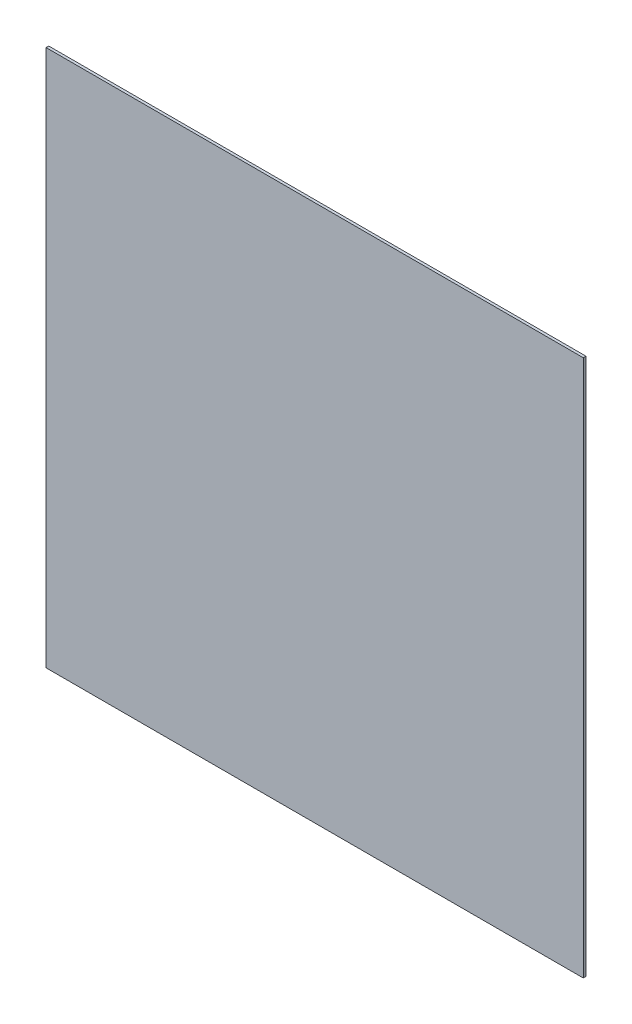
SolidWorks part; units mm, degrees
ref_plane "Front Plane" through (0, 0, 0) normal (0, 0, 1) x (1, 0, 0)
ref_plane "Top Plane" through (0, 0, 0) normal (0, 1, 0) x (1, 0, 0)
ref_plane "Right Plane" through (0, 0, 0) normal (1, 0, 0) x (0, 0, -1)
sketch "Sketch1" plane through (0, 0, 0) normal (0, 0, 1) x (1, 0, 0)
  line L0 (-500, -1008) -> (-500, -8) construction
  line L1 (500, -1008) -> (-500, -1008)
  line L2 (500, -1008) -> (500, -8)
  line L3 (500, -8) -> (-500, -8)
  line L4 (-500, -1008) -> (-500, -8)
  line L5 (500, -1008) -> (-500, -8) construction
  line L6 (500, -8) -> (-500, -1008) construction
  point P0 (0, -508)
extrude "Extrude1" add sketch "Sketch1" against normal blind 5
